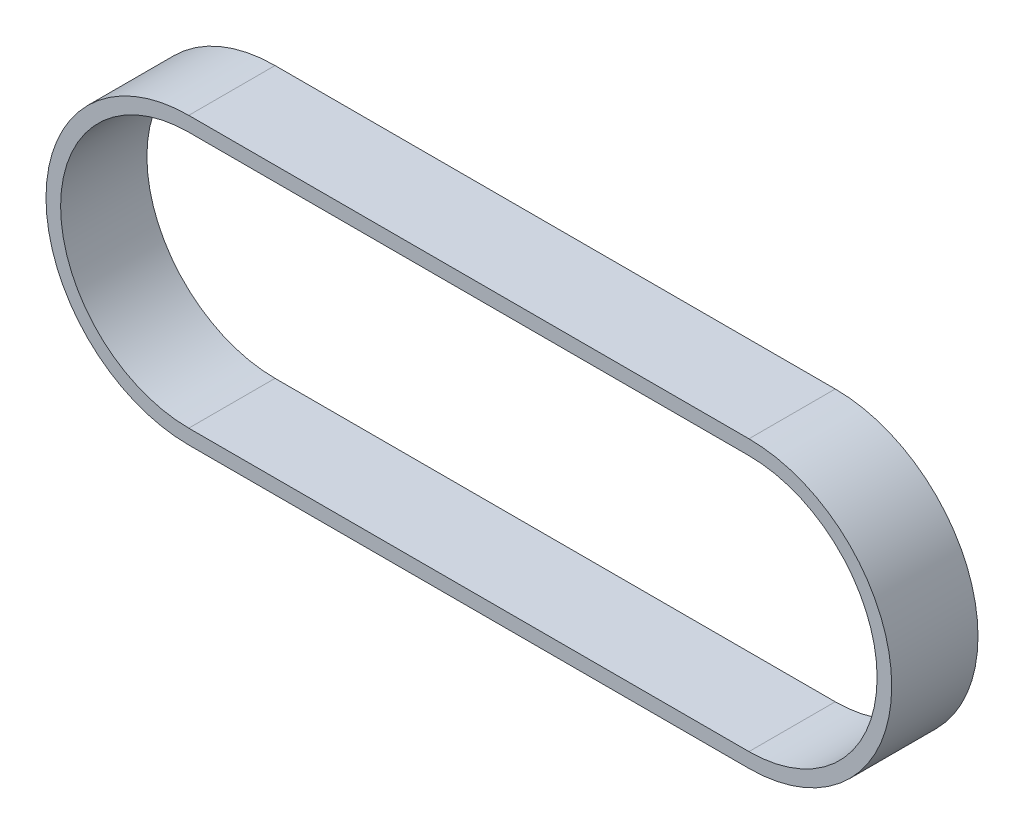
SolidWorks part; units mm, degrees
ref_plane "Front Plane" through (0, 0, 0) normal (0, 0, 1) x (1, 0, 0)
ref_plane "Top Plane" through (0, 0, 0) normal (0, 1, 0) x (1, 0, 0)
ref_plane "Right Plane" through (0, 0, 0) normal (1, 0, 0) x (0, 0, -1)
sketch "Sketch1" plane through (0, 0, 0) normal (0, 0, 1) x (1, 0, 0)
  line L0 (97.3836, 0) -> (0, 0) construction
  line L1 (0, 22.2758) -> (97.3836, 22.2758)
  line L2 (97.3836, -22.2758) -> (0, -22.2758)
  line L3 (48.6918, 22.2758) -> (48.6918, 2.5582) construction
  line L4 (0, 24.8158) -> (97.3836, 24.8158)
  line L5 (97.3836, -24.8158) -> (0, -24.8158)
  circle A0 centre (0, 0) radius 22.2758 construction
  circle A1 centre (97.3836, 0) radius 22.2758 construction
  arc A2 (0, -22.2758) -> (0, 22.2758) centre (0, 0) cw
  arc A3 (97.3836, -22.2758) -> (97.3836, 22.2758) centre (97.3836, 0) ccw
  arc A4 (97.3836, -24.8158) -> (97.3836, 24.8158) centre (97.3836, 0) ccw
  arc A5 (0, -24.8158) -> (0, 24.8158) centre (0, 0) cw
  dimension "D1" = 44.5516
  dimension "D2" = 97.3836
  dimension "D3" = 2.54
extrude "Boss-Extrude1" add sketch "Sketch1" along normal blind 15
